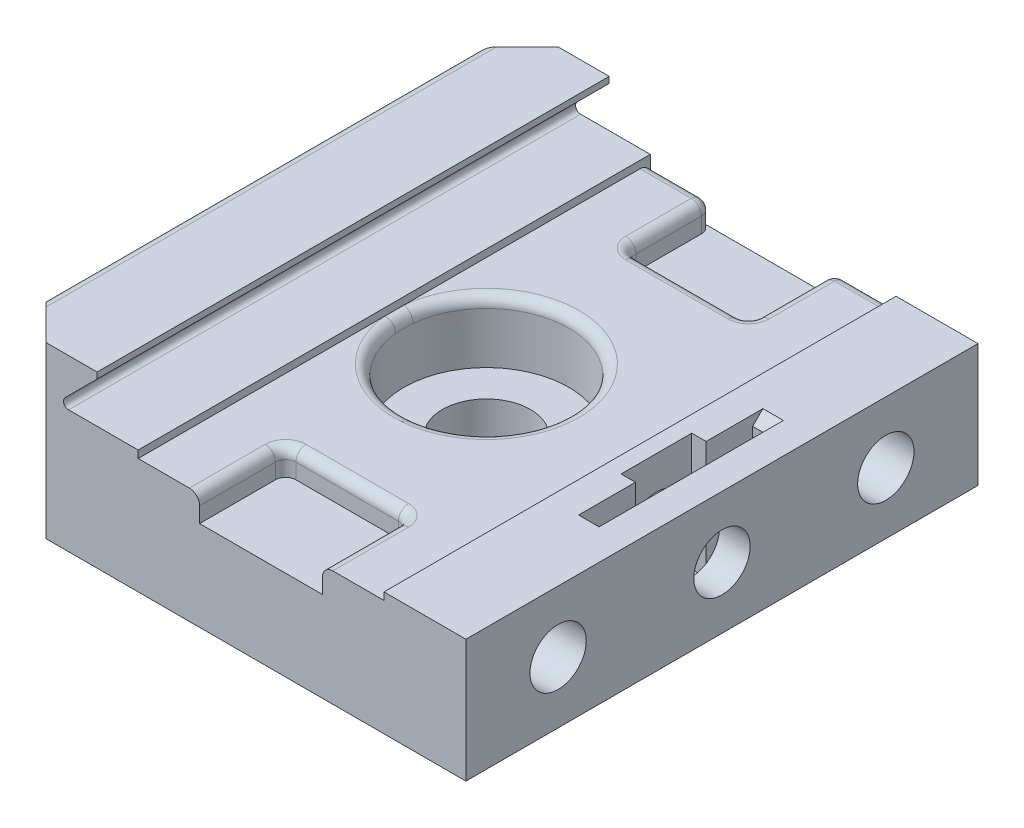
SolidWorks part; units mm, degrees
ref_plane "Front Plane" through (0, 0, 0) normal (0, 0, 1) x (1, 0, 0)
ref_plane "Top Plane" through (0, 0, 0) normal (0, 1, 0) x (1, 0, 0)
ref_plane "Right Plane" through (0, 0, 0) normal (1, 0, 0) x (0, 0, -1)
sketch "Sketch1" plane through (0, 0, 0) normal (0, 1, 0) x (1, 0, 0)
  line L1 (22.5, -25) -> (-22.5, -25)
  line L2 (22.5, -25) -> (22.5, 25)
  line L3 (22.5, 25) -> (-22.5, 25)
  line L4 (-22.5, -25) -> (-22.5, 25)
  line L5 (22.5, -25) -> (-22.5, 25) construction
  line L6 (22.5, 25) -> (-22.5, -25) construction
  point P0 (0, 0)
  dimension "D1" = 45
  dimension "D2" = 50
extrude "Boss-Extrude1" add sketch "Sketch1" along normal blind 16
sketch "Sketch3" plane through (0, 0, 25) normal (0, 0, 1) x (1, 0, 0)
  line L0 (-13.5, 16) -> (-17.5, 12)
  line L1 (22.5, 16) -> (-13.5, 16)
  line L2 (22.5, 16) -> (22.5, 12)
  line L3 (22.5, 12) -> (-17.5, 12)
  dimension "D1" = 40
  dimension "D2" = 36
  dimension "D3" = 45
extrude "Cut-Extrude1" cut sketch "Sketch3" against normal through all
sketch "Sketch4" plane through (0, 12, 0) normal (0, 1, 0) x (1, 0, 0)
  line L0 (22.5, 25) -> (-17.5, -25) construction
  line L1 (-17.5, -25) -> (22.5, -25)
  line L2 (-17.5, -25) -> (-17.5, 25)
  line L3 (-17.5, 25) -> (22.5, 25)
  line L4 (22.5, -25) -> (22.5, 25)
  line L5 (22.5, -25) -> (-17.5, 25) construction
  line L7 (-9.5, -25) -> (14.5, -25)
  line L8 (-9.5, -25) -> (-9.5, 25)
  line L9 (-9.5, 25) -> (14.5, 25)
  line L10 (14.5, -25) -> (14.5, 25)
  line L11 (-9.5, -25) -> (14.5, 25) construction
  line L12 (-9.5, 25) -> (14.5, -25) construction
  point P6 (2.5, 0)
  dimension "D1" = 24
extrude "Cut-Extrude2" cut sketch "Sketch4" against normal blind 0.72 contours L8 L9 L10 L7
sketch "Sketch5" plane through (0, 0, 25) normal (0, 0, 1) x (1, 0, 0)
  line L0 (-22.5, 16) -> (-13.5, 16)
  line L1 (-13.5, 16) -> (-13.51, 15.99)
  line L2 (-13.5, 16) -> (-17.5, 12) construction
  line L3 (-13.51, 15.99) -> (-22.5, 15.99)
  line L4 (-22.5, 16) -> (-22.5, 0) construction
  line L5 (-22.5, 15.99) -> (-22.5, 16)
  dimension "D1" = 0.01
extrude "Cut-Extrude3" cut sketch "Sketch5" against normal through all
sketch "Sketch8" plane through (0, 11.28, 0) normal (0, 1, 0) x (1, 0, 0)
  line L0 (-9.5, -25) -> (-9.5, 25) construction
  line L1 (-9.5, -25) -> (14.5, -25) construction
  circle A0 centre (-0.5, 0) radius 8.05
  dimension "D1" = 9
  dimension "D3" = 16.1
  dimension "D2" = 25
extrude "Cut-Extrude4" cut sketch "Sketch8" against normal blind 6
hole_wizard "M8 Clearance Hole1" positions "Sketch9" profile "Sketch10" hole size "M8" standard "ANSI Metric" end condition through all
sketch "Sketch9" plane through (0, 5.28, 0) normal (0, 1, 0) x (1, 0, 0)
  point P0 (-0.5, 0)
sketch "Sketch10" plane through (-0.5, 5.28, 0) normal (1, 0, 0) x (0, 0, 1)
  line L0 (0, 0) -> (0, 5.28)
  line L1 (0, 5.28) -> (4.3, 5.28)
  line L2 (4.3, 5.28) -> (4.3, 0)
  line L5 (4.3, 0) -> (0, 0)
  line L11 (0, -6.35) -> (0, 107.95) construction
  dimension "Thru Hole Dia." = 8.6
  dimension "Thru Hole Depth" = 5.28
sketch "Sketch12" plane through (0, 11.28, 0) normal (0, 1, 0) x (1, 0, 0)
  line L0 (-9.5, 25) -> (14.5, 25) construction
  line L1 (7.5, 16.6) -> (-2.5, 16.6)
  line L2 (8.5, 17.6) -> (8.5, 25)
  line L4 (-3.5, 17.6) -> (-3.5, 25)
  line L5 (-3.5, 21.3) -> (8.5, 21.3) construction
  line L6 (2.5, 25) -> (2.5, 16.6) construction
  line L7 (-3.5, 25) -> (8.5, 25)
  line L8 (-9.5, -25) -> (-9.5, 25) construction
  arc A0 (7.5, 16.6) -> (8.5, 17.6) centre (7.5, 17.6) ccw
  arc A1 (-2.5, 16.6) -> (-3.5, 17.6) centre (-2.5, 17.6) cw
  point P0 (2.5, 25)
  point P9 (8.5, 16.6)
  point P12 (-3.5, 16.6)
  point P17 (2.5, 21.3)
  dimension "D2" = 1
  dimension "D1" = 12
  dimension "D3" = 12
  dimension "D4" = 0
  dimension "D5" = 7.4
extrude "Cut-Extrude5" cut sketch "Sketch12" against normal blind 2.5
fillet "Fillet1" radius 1 2 edges at (8.5, 10.03, -25) (-3.5, 10.03, -25)
mirror "Mirror2" about plane through (0, 0, 0) normal (0, 0, 1) of "Cut-Extrude5"
fillet "Fillet2" radius 1 15 edges at (-7, 11.28, -25) (-3.7929, 11.28, -24.7071) (12, 11.28, -25) (8.7929, 11.28, -24.7071) (8.5, 11.28, -20.8) (8.2071, 11.28, -16.8929) (2.5, 11.28, -16.6) (-3.2071, 11.28, -16.8929) (-3.5, 11.28, 21.3) (-3.2071, 11.28, 16.8929) (8.5, 11.28, 21.3) (8.2071, 11.28, 16.8929) (-8.55, 11.28, 0) (-3.5, 11.28, -20.8) (2.5, 11.28, 16.6)
fillet "Fillet4" radius 0.5 1 edges at (-17.5, 12, 0)
sketch "Sketch14" plane through (0, 12, 0) normal (0, 1, 0) x (1, 0, 0)
  line L0 (14.5, 25) -> (22.5, 25) construction
  line L1 (19.5, -8) -> (17.5, -8)
  line L2 (19.5, -8) -> (19.5, 8)
  line L3 (19.5, 8) -> (17.5, 8)
  line L4 (17.5, -8) -> (17.5, -3.45)
  line L5 (19.5, -8) -> (17.5, 8) construction
  line L6 (19.5, 8) -> (17.5, -8) construction
  line L7 (17.5, 3.45) -> (16.1, 3.45)
  line L8 (17.5, -3.45) -> (16.1, -3.45)
  line L11 (16.1, -3.45) -> (16.1, 3.45)
  line L12 (19.5, -1.4375) -> (16.1, 3.45) construction
  line L13 (19.5, 1.4375) -> (16.1, -3.45) construction
  line L14 (17.5, 3.45) -> (17.5, 8)
  point P0 (18.5, 0)
  point P7 (18.5, 0)
  dimension "D1" = 16
  dimension "D2" = 25
  dimension "D3" = 2
  dimension "D4" = 6.9
  dimension "D5" = 1.4
  dimension "D6" = 4.55
extrude "Cut-Extrude7" cut sketch "Sketch14" against normal blind 11.5
sketch "Sketch18" plane through (22.5, 0, 0) normal (1, 0, 0) x (0, 0, -1)
  circle A0 centre (0, 6) radius 2.75
  dimension "D1" = 5.5
extrude "Cut-Extrude8" cut sketch "Sketch18" against normal blind 14.5
sketch "Sketch19" plane through (22.5, 0, 0) normal (1, 0, 0) x (0, 0, -1)
  line L0 (-25, 12) -> (-25, 0) construction
  line L1 (25, 12) -> (25, 0) construction
  circle A0 centre (-16, 6) radius 2.75
  circle A1 centre (16, 6) radius 2.75
  dimension "D3" = 5.5
  dimension "D4" = 5.5
  dimension "D1" = 9
  dimension "D2" = 9
extrude "Cut-Extrude9" cut sketch "Sketch19" against normal blind 10
sketch "Sketch20" plane through (0, 0, 0) normal (0, -1, 0) x (-1, 0, 0)
  line L1 (-4.65, 8.25) -> (-0.35, 8.25)
  line L2 (-4.65, 8.25) -> (-4.65, -8.25)
  line L3 (-4.65, -8.25) -> (-0.35, -8.25)
  line L4 (-0.35, 8.25) -> (-0.35, -8.25)
  line L5 (-4.65, 8.25) -> (-0.35, -8.25) construction
  line L6 (-4.65, -8.25) -> (-0.35, 8.25) construction
  dimension "D1" = 4.3
  dimension "D2" = 16.5
extrude "Cut-Extrude10" [suppressed] cut sketch "Sketch20" against normal blind 2
sketch "Sketch21" plane through (0, 15.99, 0) normal (0, 1, 0) x (1, 0, 0)
  line L1 (-22.5, 25) -> (-13.51, 25)
  line L2 (-22.5, 25) -> (-22.5, -25)
  line L3 (-22.5, -25) -> (-13.51, -25)
  line L4 (-13.51, 25) -> (-13.51, -25)
extrude "Boss-Extrude2" add sketch "Sketch21" along normal blind 0.6
chamfer "Chamfer1" distance 4 angle 45 2 edges at (-22.5, 8.295, -25) (-22.5, 8.295, 25)
fillet "Fillet5" radius 1 1 edges at (-22.5, 16.59, 0)
sketch "Sketch23" plane through (0, 5.28, 0) normal (0, 1, 0) x (1, 0, 0)
  line L1 (-0.5, 6.6188) -> (-6.2321, 3.3094)
  line L2 (-6.2321, 3.3094) -> (-6.2321, -3.3094)
  line L3 (-6.2321, -3.3094) -> (-0.5, -6.6188)
  line L4 (-0.5, -6.6188) -> (5.2321, -3.3094)
  line L5 (5.2321, -3.3094) -> (5.2321, 3.3094)
  line L6 (5.2321, 3.3094) -> (-0.5, 6.6188)
  circle A0 centre (-0.5, 0) radius 5.7321 construction
extrude "Cut-Extrude11" [suppressed] cut sketch "Sketch23" against normal blind 4
chamfer "Chamfer2" distance 1 angle 45 2 edges at (18.5, 12, 8) (18.5, 12, -8)
